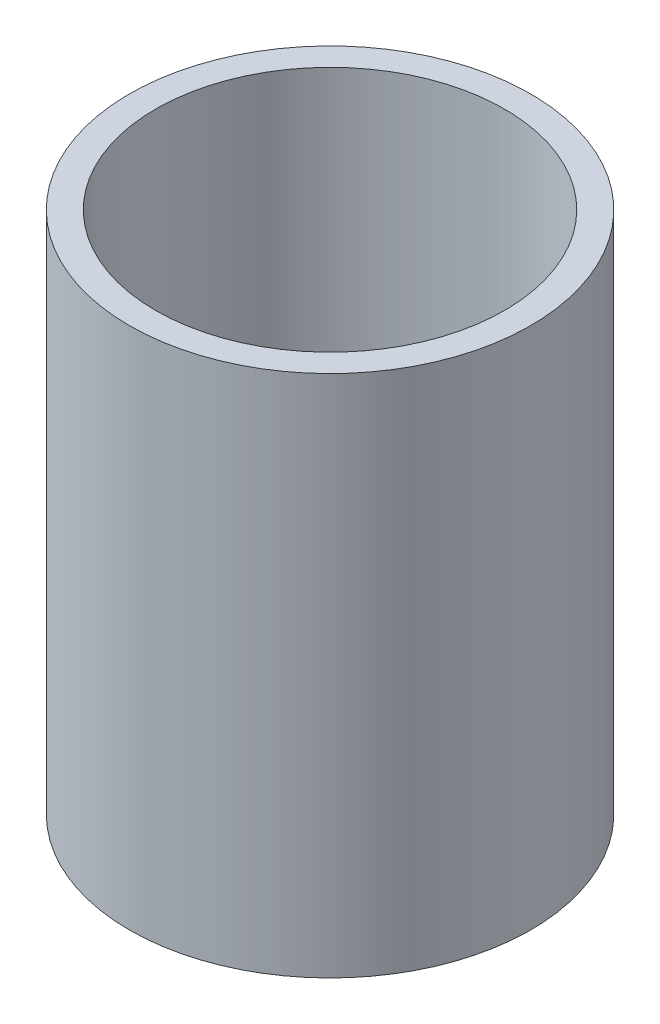
SolidWorks part; units mm, degrees
ref_plane "Front Plane" through (0, 0, 0) normal (0, 0, 1) x (1, 0, 0)
ref_plane "Top Plane" through (0, 0, 0) normal (0, 1, 0) x (1, 0, 0)
ref_plane "Right Plane" through (0, 0, 0) normal (1, 0, 0) x (0, 0, -1)
sketch "Sketch1" plane through (0, 0, 0) normal (0, 1, 0) x (1, 0, 0)
  circle A0 centre (0, 0) radius 23
  dimension "D1" = 46
extrude "Boss-Extrude1" add sketch "Sketch1" along normal blind 60
sketch "Sketch2" plane through (0, 0, 0) normal (0, -1, 0) x (1, 0, 0)
  circle A0 centre (0, 0) radius 20
  dimension "D1" = 40
extrude "Cut-Extrude1" cut sketch "Sketch2" against normal blind 22
sketch "Sketch4" plane through (0, 22, 0) normal (0, -1, 0) x (1, 0, 0)
  circle A0 centre (0, 0) radius 2
  dimension "D1" = 4
sketch "Sketch5" plane through (0, 60, 0) normal (0, 1, 0) x (1, 0, 0)
  circle A0 centre (0, 0) radius 20
  dimension "D1" = 40
extrude "Cut-Extrude2" cut sketch "Sketch5" against normal blind 32
extrude "Cut-Extrude3" cut sketch "Sketch4" against normal blind 40
